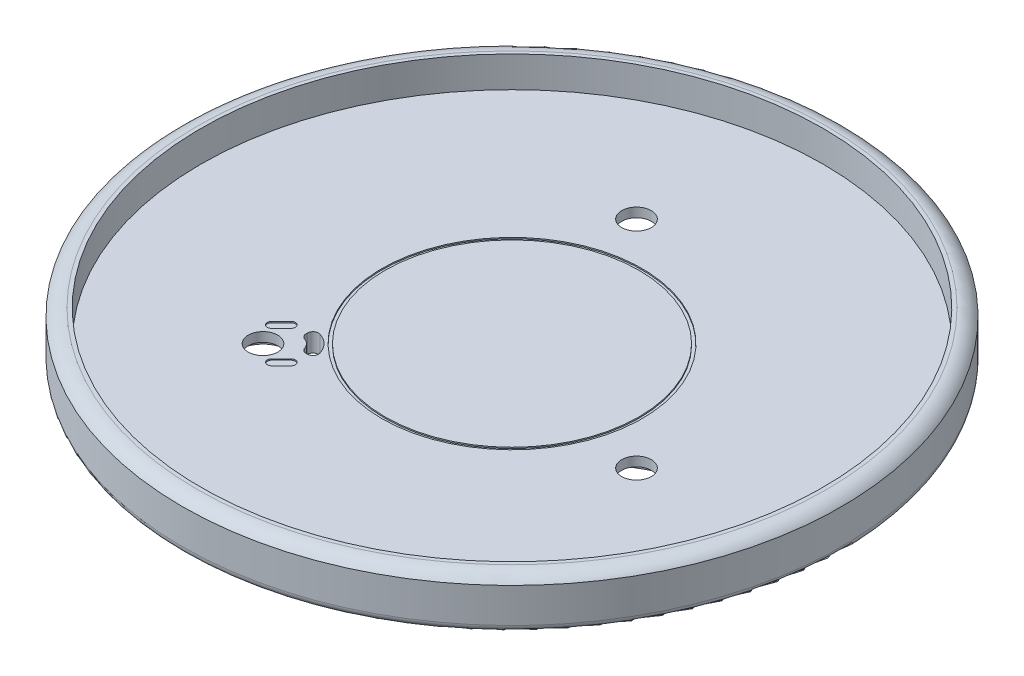
SolidWorks part; units mm, degrees
ref_plane "前视基准面" through (0, 0, 0) normal (0, 0, 1) x (1, 0, 0)
ref_plane "上视基准面" through (0, 0, 0) normal (0, 1, 0) x (1, 0, 0)
ref_plane "右视基准面" through (0, 0, 0) normal (1, 0, 0) x (0, 0, -1)
sketch "草图1" plane through (0, 0, 0) normal (0, 1, 0) x (1, 0, 0)
  circle A0 centre (0, 0) radius 50.2
  circle A1 centre (0, 0) radius 20.5 construction
  dimension "D1" = 100.4
  dimension "D2" = 41
extrude "凸台-拉伸1" add sketch "草图1" along normal blind 3
sketch "草图3" plane through (0, 0, 0) normal (0, -1, 0) x (1, 0, 0)
  circle A0 centre (0, 0) radius 53.2
  circle A1 centre (0, 0) radius 50.2 construction
  circle A2 centre (0, 0) radius 50.2
  dimension "D1" = 3
extrude "凸台-拉伸2" add sketch "草图3" against normal blind 8
sketch "草图4" plane through (0, 3, 0) normal (0, 1, 0) x (1, 0, 0)
  line L0 (-37.8336, 0) -> (34.4444, 0) construction
  line L1 (0, 37.4001) -> (0, -32.3556) construction
  circle A0 centre (0, 0) radius 20.5
  circle A1 centre (0, 0) radius 21
  dimension "D1" = 41
  dimension "D2" = 42
extrude "切除-拉伸1" cut sketch "草图4" against normal blind 0.2
sketch "草图5" plane through (0, 0, 0) normal (1, 0, 0) x (0, 0, -1)
  line L0 (53.2, 6.8) -> (53.2, 8)
  line L2 (53.2, 8) -> (50.8, 8)
  line L3 (50.2, 8) -> (-50.2, 8) construction
  line L4 (0, 0) -> (0, 12.9368)
  arc A0 (50.8, 8) -> (53.2, 6.8) centre (50.8, 5) cw
  dimension "D1" = 1.2
  dimension "D2" = 2.4
revolve "切除-旋转1" cut sketch "草图5" angle 360 about L4
fillet "圆角2" radius 1.2 1 edges at (0, 0, -53.2)
sketch "草图6" plane through (0, 0, 0) normal (0, -1, 0) x (1, 0, 0)
  line L0 (-29.5028, 0) -> (27.9284, 0) construction
  line L1 (0, 23.6501) -> (0, -22.1442) construction
  line L2 (-26, 23.2) -> (-23.8509, 18.3731)
  line L3 (-24, 26) -> (-18, 26)
  line L4 (-26, 24) -> (-26, 19)
  line L5 (-20.1967, 16) -> (-18, 16)
  line L6 (-16, 20.1967) -> (-16, 18)
  line L7 (-23.2, 26) -> (-18.3731, 23.8509)
  line L8 (33.0918, 10.9167) -> (27.837, 11.469)
  line L9 (33.7846, 10.5167) -> (29.4545, 13.0167)
  line L10 (34.5167, 7.7846) -> (31.5167, 2.5885)
  line L11 (34.1167, 7.0918) -> (29.842, 3.9861)
  line L12 (25.4909, 3.758) -> (23.5885, 4.8564)
  line L13 (23.9548, 9.4909) -> (22.8564, 7.5885)
  line L14 (-7.0918, -34.1167) -> (-3.9861, -29.842)
  line L15 (-7.7846, -34.5167) -> (-3.4545, -32.0167)
  line L16 (-10.5167, -33.7846) -> (-13.5167, -28.5885)
  line L17 (-10.9167, -33.0918) -> (-11.469, -27.837)
  line L18 (-9.4909, -23.9548) -> (-7.5885, -22.8564)
  line L19 (-3.758, -25.4909) -> (-4.8564, -23.5885)
  arc A0 (-26, 24) -> (-24, 26) centre (-24, 24) cw
  arc A1 (-18, 16) -> (-16, 18) centre (-18, 18) ccw
  arc A2 (-16, 20.1967) -> (-18.3731, 23.8509) centre (-20, 20.1967) ccw
  arc A3 (-23.8509, 18.3731) -> (-20.1967, 16) centre (-20.1967, 20) ccw
  arc A4 (33.7846, 10.5167) -> (34.5167, 7.7846) centre (32.7846, 8.7846) cw
  arc A5 (25.4909, 3.758) -> (29.842, 3.9861) centre (27.4909, 7.2221) ccw
  arc A6 (22.8564, 7.5885) -> (23.5885, 4.8564) centre (24.5885, 6.5885) ccw
  arc A7 (27.837, 11.469) -> (23.9548, 9.4909) centre (27.4189, 7.4909) ccw
  arc A8 (-7.7846, -34.5167) -> (-10.5167, -33.7846) centre (-8.7846, -32.7846) cw
  arc A9 (-9.4909, -23.9548) -> (-11.469, -27.837) centre (-7.4909, -27.4189) ccw
  arc A10 (-4.8564, -23.5885) -> (-7.5885, -22.8564) centre (-6.5885, -24.5885) ccw
  arc A11 (-3.9861, -29.842) -> (-3.758, -25.4909) centre (-7.2221, -27.4909) ccw
  point P11 (-26, 26)
  point P18 (-16, 16)
  point P58 (0, 0)
  dimension "D5" = 2
  dimension "D10" = 2
  dimension "D3" = 4
  dimension "D1" = 16
  dimension "D2" = 16
  dimension "D4" = 10
  dimension "D6" = 24
  dimension "D7" = 24
  dimension "D8" = 0.8
  dimension "D9" = 0.8
  dimension "D11" = 10
  dimension "D12" = 3
extrude "切除-拉伸2" cut sketch "草图6" against normal blind 1.5 contours L14 A11 L19 A10 L18 A9 L17 L16 A8 L15 | L8 A7 L13 A6 L12 A5 L11 L10 A4 L9 | L2 A3 L5 A1 L6 A2 L7 L3 A0 L4
sketch "草图7" plane through (0, 0, 0) normal (0, -1, 0) x (1, 0, 0)
  line L0 (0, 0) -> (-25.4142, 25.4142) construction
  line L1 (-18, 15.0335) -> (-18, 15.2432)
  line L2 (-15.0335, 18) -> (-15.2432, 18)
  arc A0 (-24, 26) -> (-26, 24) centre (-24, 24) ccw construction
  arc A3 (-18, 16) -> (-16, 18) centre (-18, 18) ccw construction
  arc A4 (-17.3793, 16.0988) -> (-16.0988, 17.3793) centre (-18, 18) ccw
  arc A5 (-16.8387, 14.1723) -> (-14.1723, 16.8387) centre (-18, 18) ccw
  arc A6 (-18, 16) -> (-16, 18) centre (-18, 18) ccw construction
  arc A7 (-18, 15.2432) -> (-17.3793, 16.0988) centre (-17.1, 15.2432) cw
  arc A8 (-18, 14) -> (-14, 18) centre (-18, 18) ccw construction
  arc A9 (-18, 15.0335) -> (-16.8387, 14.1723) centre (-17.1, 15.0335) ccw
  arc A10 (-14.1723, 16.8387) -> (-15.0335, 18) centre (-15.0335, 17.1) ccw
  arc A11 (-15.2432, 18) -> (-16.0988, 17.3793) centre (-15.2432, 17.1) ccw
  dimension "D2" = 0.9
  dimension "D1" = 2
extrude "切除-拉伸3" cut sketch "草图7" against normal blind 10
sketch "草图8" plane through (0, 3, 0) normal (0, 1, 0) x (1, 0, 0)
  line L0 (0, 0) -> (-24.3102, -24.3102) construction
  line L1 (-16.7808, -22.0134) -> (-15.2252, -20.4578) construction
  line L2 (-17.2758, -21.5184) -> (-15.7201, -19.9628)
  line L3 (-16.2858, -22.5084) -> (-14.7302, -20.9527)
  line L4 (-22.0134, -16.7808) -> (-20.4578, -15.2252) construction
  line L5 (-21.5184, -17.2758) -> (-19.9628, -15.7201)
  line L6 (-22.5084, -16.2858) -> (-20.9527, -14.7302)
  arc A0 (-17.2758, -21.5184) -> (-16.2858, -22.5084) centre (-16.7808, -22.0134) ccw
  arc A1 (-14.7302, -20.9527) -> (-15.7201, -19.9628) centre (-15.2252, -20.4578) ccw
  arc A2 (-16.0988, -17.3793) -> (-17.3793, -16.0988) centre (-18, -18) ccw construction
  arc A3 (-16.0988, -17.3793) -> (-17.3793, -16.0988) centre (-18, -18) ccw
  arc A4 (-21.5184, -17.2758) -> (-22.5084, -16.2858) centre (-22.0134, -16.7808) cw
  arc A5 (-20.9527, -14.7302) -> (-19.9628, -15.7201) centre (-20.4578, -15.2252) cw
  point P5 (-16.003, -21.2356)
  point P16 (-21.2356, -16.003)
  dimension "D2" = 0.7
  dimension "D1" = 2.2
  dimension "D3" = 3
  dimension "D4" = 3.2
extrude "切除-拉伸4" cut sketch "草图8" against normal blind 0.2 contours A5 L6 A4 L5 | L3 A1 L2 A0
sketch "草图9" plane through (0, 3, 0) normal (0, 1, 0) x (1, 0, 0)
  line L0 (-20, -20.1967) -> (-20.1967, -20)
  line L1 (0, 0) -> (-20.0984, -20.0984) construction
  circle A0 centre (-20.0984, -20.0984) radius 2.38
  circle A1 centre (-7.3565, 27.4549) radius 2.38
  circle A2 centre (27.4549, -7.3565) radius 2.38
  dimension "D1" = 4.76
  dimension "D3" = 28.4234
  dimension "D2" = 3
extrude "切除-拉伸5" cut sketch "草图9" against normal blind 10
sketch "草图10" plane through (0, 0, 0) normal (0, -1, 0) x (1, 0, 0)
  line L0 (0, 0) -> (-15.1716, 15.1716) construction
  line L1 (-21.7279, -6.5563) -> (6.5563, 21.7279) construction
  arc A0 (-16.8387, 14.1723) -> (-14.1723, 16.8387) centre (-18, 18) ccw construction
  text T0 "<b>10</b>" font "JetBrains Mono" height 9
  point P10 (-7.5858, 7.5858)
  dimension "D1" = 20
  dimension "D2" = 40
extrude "切除-拉伸6" cut sketch "草图10" against normal blind 0.8
